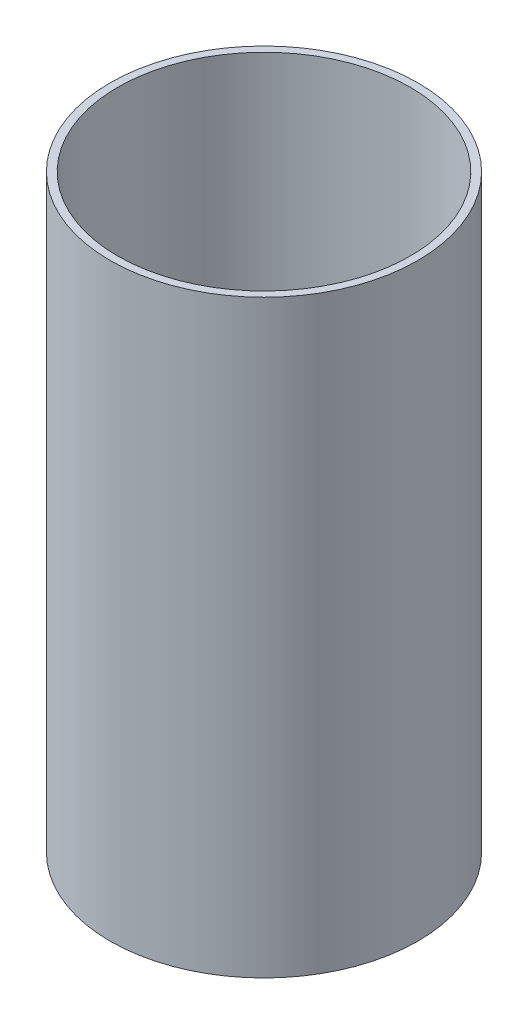
SolidWorks part; units mm, degrees
ref_plane "Front Plane" through (0, 0, 0) normal (0, 0, 1) x (1, 0, 0)
ref_plane "Top Plane" through (0, 0, 0) normal (0, 1, 0) x (1, 0, 0)
ref_plane "Right Plane" through (0, 0, 0) normal (1, 0, 0) x (0, 0, -1)
sketch "Sketch2" plane through (0, 0, 0) normal (0, 0, 1) x (1, 0, 0)
  line L0 (127, 271.5) -> (635, 271.5) construction
  line L2 (292.8789, 284.9388) -> (292.8789, 66.9378)
  line L5 (349.7789, 284.9388) -> (349.7789, 66.9378) construction
  line L6 (292.8789, 284.9388) -> (349.7789, 284.9388)
  line L7 (292.8789, 66.9378) -> (349.7789, 66.9378)
  line L8 (349.7789, 284.9388) -> (349.7789, 66.9378)
revolve "Revolve2" add sketch "Sketch2" angle 360 about L5
sketch "Sketch3" plane through (0, 284.9388, 0) normal (0, 1, 0) x (1, 0, 0)
  line L0 (292.8789, 0) -> (349.7789, 0) construction
  circle A0 centre (349.7789, 0) radius 54.0817
extrude "Cut-Extrude1" cut sketch "Sketch3" against normal blind 210
fillet "Fillet1" radius 10 1 edges at (349.7789, 74.9388, 54.0817)
